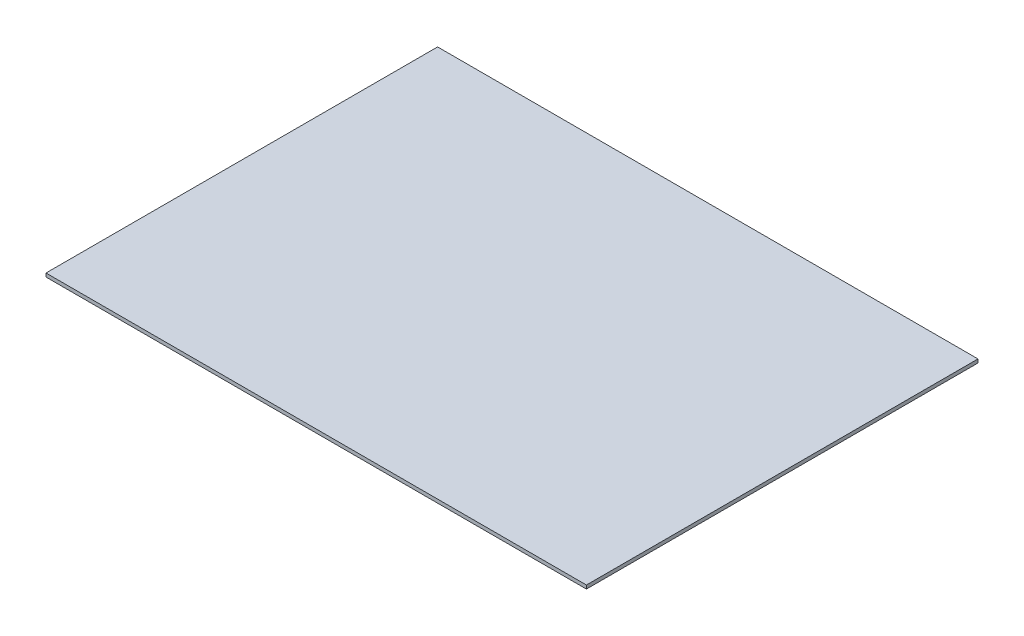
SolidWorks part; units mm, degrees
ref_plane "Front Plane" through (0, 0, 0) normal (0, 0, 1) x (1, 0, 0)
ref_plane "Top Plane" through (0, 0, 0) normal (0, 1, 0) x (1, 0, 0)
ref_plane "Right Plane" through (0, 0, 0) normal (1, 0, 0) x (0, 0, -1)
sketch "Sketch1" plane through (0, 0, 0) normal (0, 1, 0) x (1, 0, 0)
  line L1 (-762.5, 552.5) -> (762.5, 552.5)
  line L2 (-762.5, 552.5) -> (-762.5, -552.5)
  line L3 (-762.5, -552.5) -> (762.5, -552.5)
  line L4 (762.5, 552.5) -> (762.5, -552.5)
  point P7 (38.8521, -196.7883)
  dimension "D1" = 1525
  dimension "D2" = 1105
  dimension "D3" = 762.5
  dimension "D4" = 552.5
extrude "Boss-Extrude1" add sketch "Sketch1" against normal blind 10
